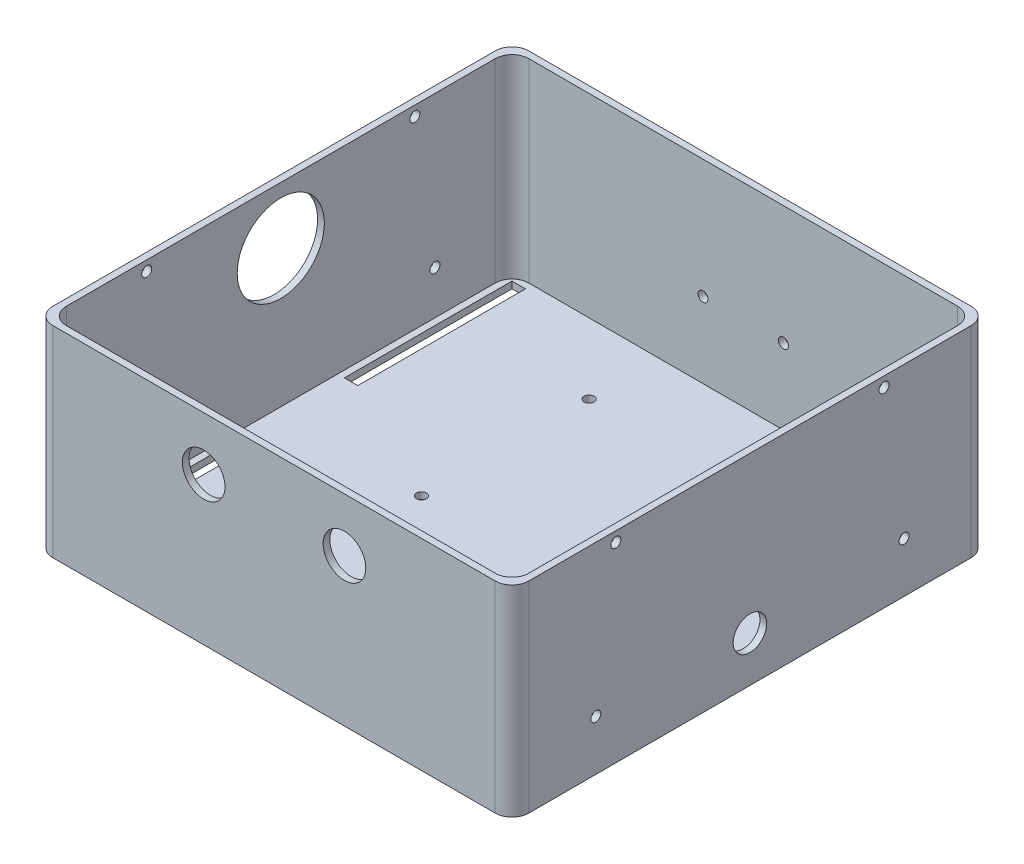
SolidWorks part; units mm, degrees
ref_plane "Front Plane" through (0, 0, 0) normal (0, 0, 1) x (1, 0, 0)
ref_plane "Top Plane" through (0, 0, 0) normal (0, 1, 0) x (1, 0, 0)
ref_plane "Right Plane" through (0, 0, 0) normal (1, 0, 0) x (0, 0, -1)
sketch "Sketch1" plane through (0, 0, 0) normal (0, 1, 0) x (1, 0, 0)
  line L1 (-71, 71) -> (71, 71)
  line L2 (-71, 71) -> (-71, -71)
  line L3 (-71, -71) -> (71, -71)
  line L4 (71, 71) -> (71, -71)
  line L5 (-71, 71) -> (71, -71) construction
  line L6 (-71, -71) -> (71, 71) construction
  point P0 (0, 0)
  dimension "D1" = 142
extrude "Boss-Extrude1" add sketch "Sketch1" along normal blind 60
sketch "Sketch2" plane through (0, 0, 71) normal (0, 0, 1) x (1, 0, 0)
  line L0 (-14, 47) -> (0, 47) construction
  line L1 (0, 47) -> (14, 47) construction
  circle A0 centre (-14, 47) radius 3
  circle A1 centre (14, 47) radius 3
  dimension "D1" = 6
  dimension "D2" = 47
  dimension "D3" = 14
sketch "Sketch3" plane through (0, 60, 0) normal (0, 1, 0) x (1, 0, 0)
  line L5 (69, 69) -> (-69, 69)
  line L6 (69, 69) -> (69, -69)
  line L7 (69, -69) -> (-69, -69)
  line L8 (-69, 69) -> (-69, -69)
  line L9 (69, 69) -> (-69, -69) construction
  line L10 (69, -69) -> (-69, 69) construction
  line L11 (-69, 69) -> (-71, 69) construction
  line L12 (-71, 71) -> (-71, -71) construction
  line L13 (-69, 69) -> (-69, 71) construction
  line L14 (71, 71) -> (-71, 71) construction
  point P0 (0, 0)
  dimension "D1" = 2
extrude "Cut-Extrude1" cut sketch "Sketch3" against normal offset from surface (58 mm away) 2 up to face at (0, 0, 0)
sketch "Sketch6" plane through (0, 0, 0) normal (0, -1, 0) x (1, 0, 0)
  circle A0 centre (0, 0) radius 5
  circle A1 centre (0, 0) radius 21.5
  dimension "D1" = 43
  dimension "D2" = 10
sketch "Sketch4" plane through (0, 0, 0) normal (0, -1, 0) x (1, 0, 0)
  line L1 (-63, -22.5) -> (-66.5, -22.5)
  line L2 (-63, -22.5) -> (-63, 22.5)
  line L3 (-63, 22.5) -> (-66.5, 22.5)
  line L4 (-66.5, -22.5) -> (-66.5, 22.5)
  line L5 (-63, -22.5) -> (-66.5, 22.5) construction
  line L6 (-63, 22.5) -> (-66.5, -22.5) construction
  line L9 (-71, -71) -> (-71, 71) construction
  point P0 (-64.75, 0)
  dimension "D1" = 4.5
  dimension "D2" = 45
  dimension "D3" = 3.5
sketch "Sketch12" plane through (0, 2, 0) normal (0, 1, 0) x (1, 0, 0)
  line L0 (-69, 69) -> (-69, -69) construction
  line L1 (-67, -17) -> (-63, -17)
  line L2 (-67, -17) -> (-67, -67)
  line L3 (-67, -67) -> (-63, -67)
  line L4 (-63, -17) -> (-63, -67)
  line L5 (-67, -17) -> (-63, -67) construction
  line L6 (-67, -67) -> (-63, -17) construction
  line L7 (-69, 0) -> (69, 0) construction
  line L8 (69, -69) -> (69, 69) construction
  line L10 (-67, 67) -> (-67, 69) construction
  line L11 (-67, 67) -> (-63, 67)
  line L12 (-67, 67) -> (-67, 17)
  line L13 (-67, 17) -> (-63, 17)
  line L14 (-63, 67) -> (-63, 17)
  line L15 (-67, 67) -> (-63, 17) construction
  line L16 (-67, 17) -> (-63, 67) construction
  line L17 (69, 69) -> (-69, 69) construction
  line L18 (-67, -67) -> (-67, -69) construction
  line L19 (-69, -69) -> (69, -69) construction
  point P0 (-65, -42)
  point P10 (-65, 42)
  point P18 (0, 0)
  dimension "D1" = 50
  dimension "D2" = 4
  dimension "D3" = 2
  dimension "D4" = 2
extrude "Cut-Extrude8" cut sketch "Sketch12" against normal through all
mirror "Mirror2" about plane through (0, 0, 0) normal (1, 0, 0) of "Cut-Extrude8"
sketch "Sketch13" plane through (0, 2, 0) normal (0, 1, 0) x (1, 0, 0)
  line L0 (-69, -69) -> (69, -69) construction
  line L1 (42, 15) -> (-42, 15) construction
  line L2 (42, 15) -> (42, -69) construction
  line L3 (42, -69) -> (-42, -69) construction
  line L4 (-42, 15) -> (-42, -69) construction
  line L5 (42, 15) -> (-42, -69) construction
  line L6 (42, -69) -> (-42, 15) construction
  line L7 (-25, -52) -> (25, -52) construction
  line L8 (-25, -52) -> (-25, -2) construction
  line L9 (-25, -2) -> (25, -2) construction
  line L10 (25, -52) -> (25, -2) construction
  line L11 (-25, -52) -> (25, -2) construction
  line L12 (-25, -2) -> (25, -52) construction
  line L13 (-63, 17) -> (-63, 67) construction
  line L14 (-63, 42) -> (-37.2775, 42) construction
  line L15 (-63, -42) -> (-37.2775, -42) construction
  line L16 (-63, -67) -> (-63, -17) construction
  line L18 (-25, -2) -> (-25, 48) construction
  line L19 (-69, 0) -> (-42, 0) construction
  line L20 (-69, -69) -> (-69, 69) construction
  circle A0 centre (-25, -2) radius 1.5
  circle A1 centre (25, -2) radius 1.5
  circle A2 centre (25, -52) radius 1.5
  circle A3 centre (-25, -52) radius 1.5
  circle A4 centre (-25, 48) radius 1.5
  circle A5 centre (25, 48) radius 1.5
  point P0 (0, -27)
  point P6 (0, -27)
  dimension "D3" = 3
  dimension "D1" = 84
  dimension "D2" = 50
  dimension "D4" = 50
extrude "Cut-Extrude9" cut sketch "Sketch13" against normal through all
sketch "Sketch9" plane through (71, 0, 0) normal (1, 0, 0) x (0, 0, -1)
  line L0 (-71, 0) -> (71, 0) construction
  circle A0 centre (0, 13.5) radius 5
  dimension "D1" = 10
  dimension "D2" = 13.5
extrude "Cut-Extrude6" cut sketch "Sketch9" against normal up to next
sketch "Sketch14" plane through (0, 0, 69) normal (0, 0, -1) x (-1, 0, 0)
  line L0 (69, 60) -> (-69, 60) construction
  line L1 (31, 44) -> (11, 44) construction
  line L2 (31, 44) -> (31, 56) construction
  line L3 (31, 56) -> (11, 56) construction
  line L4 (11, 44) -> (11, 56) construction
  line L5 (31, 44) -> (11, 56) construction
  line L6 (31, 56) -> (11, 44) construction
  line L8 (-69, 2) -> (69, 2) construction
  line L9 (16.5, 48.5) -> (25.5, 48.5) construction
  line L10 (16.5, 48.5) -> (16.5, 39.5) construction
  line L11 (16.5, 39.5) -> (25.5, 39.5) construction
  line L12 (25.5, 48.5) -> (25.5, 39.5) construction
  line L13 (16.5, 48.5) -> (25.5, 39.5) construction
  line L14 (16.5, 39.5) -> (25.5, 48.5) construction
  circle A0 centre (11, 44) radius 1 construction
  circle A1 centre (11, 56) radius 1 construction
  circle A2 centre (31, 56) radius 1 construction
  circle A3 centre (31, 44) radius 1 construction
  circle A4 centre (21, 44) radius 6.364
  point P0 (21, 50)
  point P13 (21, 44)
  point P20 (0, 2)
  dimension "D5" = 2
  dimension "D1" = 12
  dimension "D2" = 20
  dimension "D3" = 4
  dimension "D4" = 21
  dimension "D6" = 9
extrude "Cut-Extrude10" cut sketch "Sketch14" against normal through all
mirror "Mirror3" about plane through (0, 0, 0) normal (1, 0, 0) of "Cut-Extrude10"
sketch "Sketch16" plane through (-71, 0, 0) normal (-1, 0, 0) x (0, 0, 1)
  line L0 (-71, 30) -> (71, 30) construction
  line L1 (-71, 60) -> (-71, 0) construction
  line L2 (71, 60) -> (71, 0) construction
  line L3 (-71, 60) -> (-71, 30) construction
  circle A0 centre (0, 43) radius 13
  point P12 (-71, 45)
  dimension "D1" = 26
extrude "Cut-Extrude11" cut sketch "Sketch16" against normal up to next
sketch "Sketch18" plane through (-71, 0, 0) normal (-1, 0, 0) x (0, 0, 1)
  line L0 (-71, 30) -> (71, 30) construction
  line L1 (-71, 60) -> (-71, 0) construction
  line L2 (71, 60) -> (71, 0) construction
  line L3 (-71, 30) -> (-71, 0) construction
  line L4 (-71, 15) -> (71, 15) construction
  circle A0 centre (-46, 15) radius 1.5
  circle A1 centre (46, 15) radius 1.5
  point P10 (-71, 15)
  dimension "D1" = 3
  dimension "D2" = 25
  dimension "D3" = 25
extrude "Cut-Extrude12" cut sketch "Sketch18" against normal through all
fillet "Fillet1" radius 5 8 edges at (-69, 31, 69) (69, 31, 69) (69, 31, -69) (-69, 31, -69) (71, 30, -71) (-71, 30, -71) (71, 30, 71) (-71, 30, 71)
sketch "Sketch19" plane through (-71, 0, 0) normal (-1, 0, 0) x (0, 0, 1)
  line L1 (-40, 58.5) -> (-40, 60) construction
  line L2 (-66, 60) -> (66, 60) construction
  line L3 (-40, 57) -> (40, 57) construction
  circle A0 centre (-40, 57) radius 1.5
  circle A1 centre (40, 57) radius 1.5
  point P4 (0, 57)
  dimension "D3" = 3
  dimension "D1" = 3
  dimension "D2" = 80
extrude "Cut-Extrude13" cut sketch "Sketch19" against normal through all
sketch "Sketch20" plane through (0, 0, -69) normal (0, 0, 1) x (1, 0, 0)
  line L0 (-64, 2) -> (64, 2) construction
  line L1 (-20, 22) -> (20, 22)
  line L2 (-20, 22) -> (-20, 27)
  line L3 (-20, 27) -> (20, 27)
  line L4 (20, 22) -> (20, 27)
  line L5 (-20, 22) -> (20, 27) construction
  line L6 (-20, 27) -> (20, 22) construction
  point P0 (0, 24.5)
  point P7 (-24.7939, 32.56)
  point P8 (0, 0)
  point P10 (-24.0043, 25)
  dimension "D1" = 20
  dimension "D2" = 40
  dimension "D3" = 5
sketch "Sketch21" plane through (0, 0, -71) normal (0, 0, 1) x (1, 0, 0)
  line L0 (-20, 24.5) -> (-12, 24.5) construction
  line L4 (12, 24.5) -> (20, 24.5) construction
  line L7 (20, 27) -> (-20, 27) construction
  line L8 (20, 27) -> (20, 22) construction
  line L9 (20, 22) -> (-20, 22) construction
  line L10 (-20, 27) -> (-20, 22) construction
  line L11 (20, 27) -> (-20, 22) construction
  line L12 (20, 22) -> (-20, 27) construction
  circle A0 centre (-12, 24.5) radius 1.5
  circle A1 centre (12, 24.5) radius 1.5
  point P6 (0, 24.5)
  point P10 (0, 0)
  point P14 (-20, 24.5)
  dimension "D1" = 3
  dimension "D2" = 8
extrude "Cut-Extrude14" cut sketch "Sketch21" along normal blind 15
